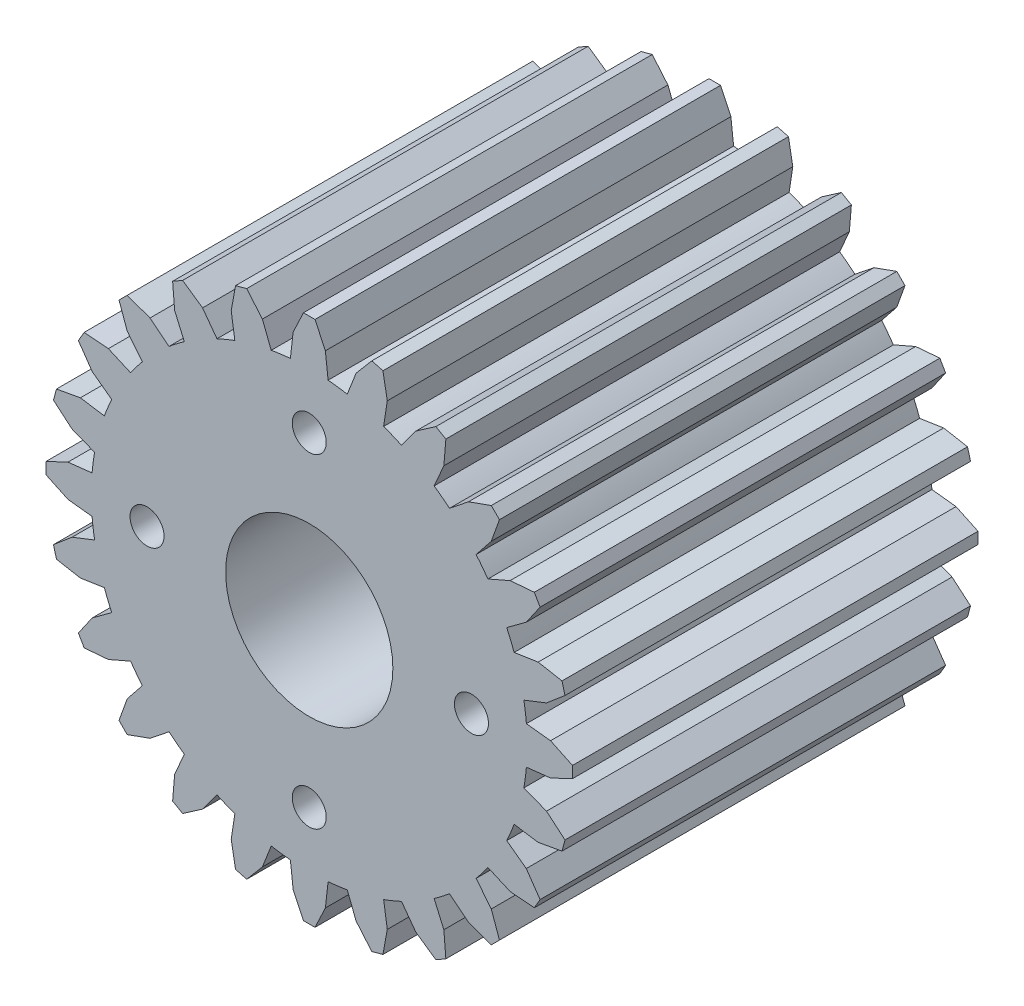
SolidWorks part; units mm, degrees
ref_plane "Plan de face" through (0, 0, 0) normal (0, 0, 1) x (1, 0, 0)
ref_plane "Plan de dessus" through (0, 0, 0) normal (0, 1, 0) x (1, 0, 0)
ref_plane "Plan de droite" through (0, 0, 0) normal (1, 0, 0) x (0, 0, -1)
sketch "Esquisse1" plane through (0, 0, 0) normal (0, 0, 1) x (1, 0, 0)
  line L0 (-1.8585, 21.4195) -> (-1.5915, 23.7996)
  line L1 (0, 2.2889) -> (0, 19223.5431) construction
  line L2 (-1.5915, 23.7996) -> (-0.5695, 25.9656)
  line L3 (-0.5695, 25.9656) -> (0.5695, 25.9656)
  line L4 (0, 0) -> (50000, 0) construction
  line L5 (1.8585, 21.4195) -> (1.5915, 23.7996)
  line L6 (1.5915, 23.7996) -> (0.5695, 25.9656)
  line L7 (3.7486, 21.1707) -> (4.6225, 23.4006)
  line L8 (4.6225, 23.4006) -> (6.1703, 25.2282)
  line L9 (7.6971, 22.5767) -> (7.2705, 24.9334)
  line L10 (7.339, 20.2087) -> (7.6971, 22.5767)
  line L11 (6.1703, 25.2282) -> (7.2705, 24.9334)
  line L12 (9.1003, 19.4791) -> (10.5215, 21.4068)
  line L13 (10.5215, 21.4068) -> (12.4896, 22.7716)
  line L14 (13.2781, 19.8153) -> (13.476, 22.2021)
  line L15 (12.3193, 17.6206) -> (13.2781, 19.8153)
  line L16 (12.4896, 22.7716) -> (13.476, 22.2021)
  line L17 (13.8317, 16.46) -> (15.7035, 17.9542)
  line L18 (15.7035, 17.9542) -> (17.9577, 18.7631)
  line L19 (17.9542, 15.7035) -> (18.7631, 17.9577)
  line L20 (16.46, 13.8317) -> (17.9542, 15.7035)
  line L21 (17.9577, 18.7631) -> (18.7631, 17.9577)
  line L22 (17.6206, 12.3193) -> (19.8153, 13.2781)
  line L23 (19.8153, 13.2781) -> (22.2021, 13.476)
  line L24 (21.4068, 10.5215) -> (22.7716, 12.4896)
  line L25 (19.4791, 9.1003) -> (21.4068, 10.5215)
  line L26 (22.2021, 13.476) -> (22.7716, 12.4896)
  line L27 (20.2087, 7.339) -> (22.5767, 7.6971)
  line L28 (22.5767, 7.6971) -> (24.9334, 7.2705)
  line L29 (23.4006, 4.6225) -> (25.2282, 6.1703)
  line L30 (21.1707, 3.7486) -> (23.4006, 4.6225)
  line L31 (24.9334, 7.2705) -> (25.2282, 6.1703)
  line L32 (21.4195, 1.8585) -> (23.7996, 1.5915)
  line L33 (23.7996, 1.5915) -> (25.9656, 0.5695)
  line L34 (23.7996, -1.5915) -> (25.9656, -0.5695)
  line L35 (21.4195, -1.8585) -> (23.7996, -1.5915)
  line L36 (25.9656, 0.5695) -> (25.9656, -0.5695)
  line L37 (21.1707, -3.7486) -> (23.4006, -4.6225)
  line L38 (23.4006, -4.6225) -> (25.2282, -6.1703)
  line L39 (22.5767, -7.6971) -> (24.9334, -7.2705)
  line L40 (20.2087, -7.339) -> (22.5767, -7.6971)
  line L41 (25.2282, -6.1703) -> (24.9334, -7.2705)
  line L42 (19.4791, -9.1003) -> (21.4068, -10.5215)
  line L43 (21.4068, -10.5215) -> (22.7716, -12.4896)
  line L44 (19.8153, -13.2781) -> (22.2021, -13.476)
  line L45 (17.6206, -12.3193) -> (19.8153, -13.2781)
  line L46 (22.7716, -12.4896) -> (22.2021, -13.476)
  line L47 (16.46, -13.8317) -> (17.9542, -15.7035)
  line L48 (17.9542, -15.7035) -> (18.7631, -17.9577)
  line L49 (15.7035, -17.9542) -> (17.9577, -18.7631)
  line L50 (13.8317, -16.46) -> (15.7035, -17.9542)
  line L51 (18.7631, -17.9577) -> (17.9577, -18.7631)
  line L52 (12.3193, -17.6206) -> (13.2781, -19.8153)
  line L53 (13.2781, -19.8153) -> (13.476, -22.2021)
  line L54 (10.5215, -21.4068) -> (12.4896, -22.7716)
  line L55 (9.1003, -19.4791) -> (10.5215, -21.4068)
  line L56 (13.476, -22.2021) -> (12.4896, -22.7716)
  line L57 (7.339, -20.2087) -> (7.6971, -22.5767)
  line L58 (7.6971, -22.5767) -> (7.2705, -24.9334)
  line L59 (4.6225, -23.4006) -> (6.1703, -25.2282)
  line L60 (3.7486, -21.1707) -> (4.6225, -23.4006)
  line L61 (7.2705, -24.9334) -> (6.1703, -25.2282)
  line L62 (1.8585, -21.4195) -> (1.5915, -23.7996)
  line L63 (1.5915, -23.7996) -> (0.5695, -25.9656)
  line L64 (-1.5915, -23.7996) -> (-0.5695, -25.9656)
  line L65 (-1.8585, -21.4195) -> (-1.5915, -23.7996)
  line L66 (0.5695, -25.9656) -> (-0.5695, -25.9656)
  line L67 (-3.7486, -21.1707) -> (-4.6225, -23.4006)
  line L68 (-4.6225, -23.4006) -> (-6.1703, -25.2282)
  line L69 (-7.6971, -22.5767) -> (-7.2705, -24.9334)
  line L70 (-7.339, -20.2087) -> (-7.6971, -22.5767)
  line L71 (-6.1703, -25.2282) -> (-7.2705, -24.9334)
  line L72 (-9.1003, -19.4791) -> (-10.5215, -21.4068)
  line L73 (-10.5215, -21.4068) -> (-12.4896, -22.7716)
  line L74 (-13.2781, -19.8153) -> (-13.476, -22.2021)
  line L75 (-12.3193, -17.6206) -> (-13.2781, -19.8153)
  line L76 (-12.4896, -22.7716) -> (-13.476, -22.2021)
  line L77 (-13.8317, -16.46) -> (-15.7035, -17.9542)
  line L78 (-15.7035, -17.9542) -> (-17.9577, -18.7631)
  line L79 (-17.9542, -15.7035) -> (-18.7631, -17.9577)
  line L80 (-16.46, -13.8317) -> (-17.9542, -15.7035)
  line L81 (-17.9577, -18.7631) -> (-18.7631, -17.9577)
  line L82 (-17.6206, -12.3193) -> (-19.8153, -13.2781)
  line L83 (-19.8153, -13.2781) -> (-22.2021, -13.476)
  line L84 (-21.4068, -10.5215) -> (-22.7716, -12.4896)
  line L85 (-19.4791, -9.1003) -> (-21.4068, -10.5215)
  line L86 (-22.2021, -13.476) -> (-22.7716, -12.4896)
  line L87 (-20.2087, -7.339) -> (-22.5767, -7.6971)
  line L88 (-22.5767, -7.6971) -> (-24.9334, -7.2705)
  line L89 (-23.4006, -4.6225) -> (-25.2282, -6.1703)
  line L90 (-21.1707, -3.7486) -> (-23.4006, -4.6225)
  line L91 (-24.9334, -7.2705) -> (-25.2282, -6.1703)
  line L92 (-21.4195, -1.8585) -> (-23.7996, -1.5915)
  line L93 (-23.7996, -1.5915) -> (-25.9656, -0.5695)
  line L94 (-23.7996, 1.5915) -> (-25.9656, 0.5695)
  line L95 (-21.4195, 1.8585) -> (-23.7996, 1.5915)
  line L96 (-25.9656, -0.5695) -> (-25.9656, 0.5695)
  line L97 (-21.1707, 3.7486) -> (-23.4006, 4.6225)
  line L98 (-23.4006, 4.6225) -> (-25.2282, 6.1703)
  line L99 (-22.5767, 7.6971) -> (-24.9334, 7.2705)
  line L100 (-20.2087, 7.339) -> (-22.5767, 7.6971)
  line L101 (-25.2282, 6.1703) -> (-24.9334, 7.2705)
  line L102 (-19.4791, 9.1003) -> (-21.4068, 10.5215)
  line L103 (-21.4068, 10.5215) -> (-22.7716, 12.4896)
  line L104 (-19.8153, 13.2781) -> (-22.2021, 13.476)
  line L105 (-17.6206, 12.3193) -> (-19.8153, 13.2781)
  line L106 (-22.7716, 12.4896) -> (-22.2021, 13.476)
  line L107 (-16.46, 13.8317) -> (-17.9542, 15.7035)
  line L108 (-17.9542, 15.7035) -> (-18.7631, 17.9577)
  line L109 (-15.7035, 17.9542) -> (-17.9577, 18.7631)
  line L110 (-13.8317, 16.46) -> (-15.7035, 17.9542)
  line L111 (-18.7631, 17.9577) -> (-17.9577, 18.7631)
  line L112 (-12.3193, 17.6206) -> (-13.2781, 19.8153)
  line L113 (-13.2781, 19.8153) -> (-13.476, 22.2021)
  line L114 (-10.5215, 21.4068) -> (-12.4896, 22.7716)
  line L115 (-9.1003, 19.4791) -> (-10.5215, 21.4068)
  line L116 (-13.476, 22.2021) -> (-12.4896, 22.7716)
  line L117 (-7.339, 20.2087) -> (-7.6971, 22.5767)
  line L118 (-7.6971, 22.5767) -> (-7.2705, 24.9334)
  line L119 (-4.6225, 23.4006) -> (-6.1703, 25.2282)
  line L120 (-3.7486, 21.1707) -> (-4.6225, 23.4006)
  line L121 (-7.2705, 24.9334) -> (-6.1703, 25.2282)
  arc A0 (-7.339, 20.2087) -> (-9.1003, 19.4791) centre (0, 0) ccw
  arc A2 (-1.8585, 21.4195) -> (-3.7486, 21.1707) centre (0, 0) ccw
  arc A3 (3.7486, 21.1707) -> (1.8585, 21.4195) centre (0, 0) ccw
  arc A4 (9.1003, 19.4791) -> (7.339, 20.2087) centre (0, 0) ccw
  arc A5 (13.8317, 16.46) -> (12.3193, 17.6206) centre (0, 0) ccw
  arc A6 (17.6206, 12.3193) -> (16.46, 13.8317) centre (0, 0) ccw
  arc A7 (20.2087, 7.339) -> (19.4791, 9.1003) centre (0, 0) ccw
  arc A8 (21.4195, 1.8585) -> (21.1707, 3.7486) centre (0, 0) ccw
  arc A9 (21.1707, -3.7486) -> (21.4195, -1.8585) centre (0, 0) ccw
  arc A10 (19.4791, -9.1003) -> (20.2087, -7.339) centre (0, 0) ccw
  arc A11 (16.46, -13.8317) -> (17.6206, -12.3193) centre (0, 0) ccw
  arc A12 (12.3193, -17.6206) -> (13.8317, -16.46) centre (0, 0) ccw
  arc A13 (7.339, -20.2087) -> (9.1003, -19.4791) centre (0, 0) ccw
  arc A14 (1.8585, -21.4195) -> (3.7486, -21.1707) centre (0, 0) ccw
  arc A15 (-3.7486, -21.1707) -> (-1.8585, -21.4195) centre (0, 0) ccw
  arc A16 (-9.1003, -19.4791) -> (-7.339, -20.2087) centre (0, 0) ccw
  arc A17 (-13.8317, -16.46) -> (-12.3193, -17.6206) centre (0, 0) ccw
  arc A18 (-17.6206, -12.3193) -> (-16.46, -13.8317) centre (0, 0) ccw
  arc A19 (-20.2087, -7.339) -> (-19.4791, -9.1003) centre (0, 0) ccw
  arc A20 (-21.4195, -1.8585) -> (-21.1707, -3.7486) centre (0, 0) ccw
  arc A21 (-21.1707, 3.7486) -> (-21.4195, 1.8585) centre (0, 0) ccw
  arc A22 (-19.4791, 9.1003) -> (-20.2087, 7.339) centre (0, 0) ccw
  arc A23 (-16.46, 13.8317) -> (-17.6206, 12.3193) centre (0, 0) ccw
  arc A24 (-12.3193, 17.6206) -> (-13.8317, 16.46) centre (0, 0) ccw
  point P17 (0, 25.9656)
  point P156 (0, 0)
  dimension "D1" = 43
  dimension "D3" = 2.395
  dimension "D4" = 83.6
  dimension "D5" = 1.8585
  dimension "D6" = 2.395
  dimension "D7" = 0.5695
  dimension "D8" = 24
extrude "Boss.-Extru.1" add sketch "Esquisse1" along normal blind 20
scale "Echelle1" scale about centroid uniform scaling no x scale factor 0.5 y scale factor 0.5 z scale factor 1
sketch "Esquisse2" plane through (0, 0, 20) normal (0, 0, 1) x (1, 0, 0)
  circle A3 centre (0, 0) radius 8 construction
  circle A4 centre (0, 8) radius 0.8387
  circle A5 centre (0, 0) radius 4.125
  circle A6 centre (8, 0) radius 0.8387
  circle A7 centre (0, -8) radius 0.8387
  circle A8 centre (-8, 0) radius 0.8387
  point P16 (0, 0)
  dimension "D1" = 16
  dimension "D2" = 1.6774
  dimension "D3" = 8.25
  dimension "D4" = 4
extrude "Enlèv. mat.-Extru.3" cut sketch "Esquisse2" against normal up to surface (20 mm away) up to face at (0, 0, 0)
